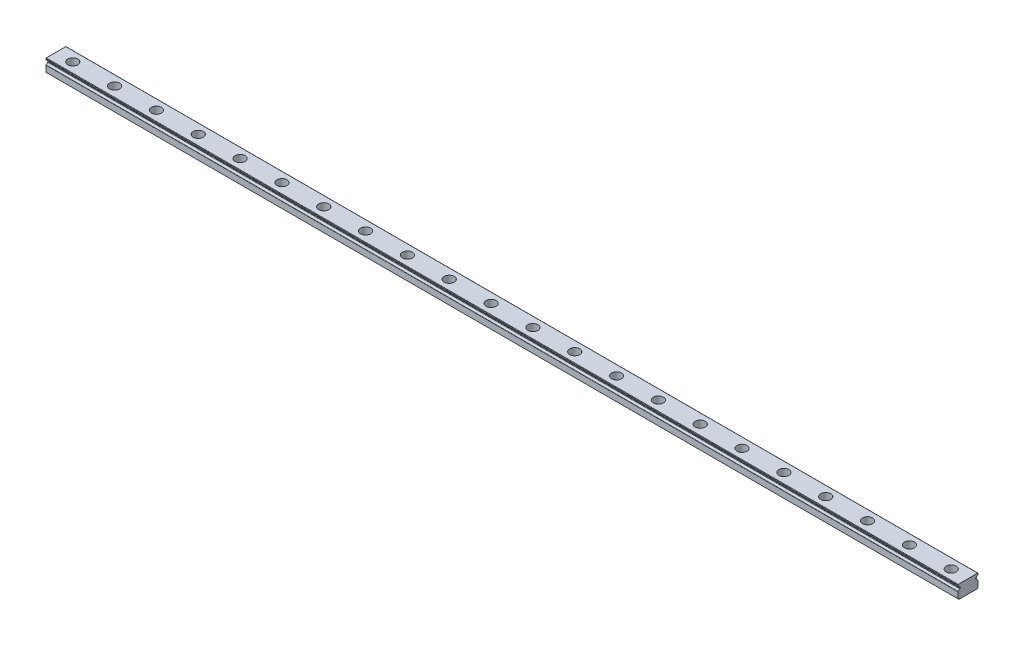
SolidWorks part; units mm, degrees
ref_plane "前视基准面" through (0, 0, 0) normal (0, 0, 1) x (1, 0, 0)
ref_plane "上视基准面" through (0, 0, 0) normal (0, 1, 0) x (1, 0, 0)
ref_plane "右视基准面" through (0, 0, 0) normal (1, 0, 0) x (0, 0, -1)
other "Configuration Table"
ref_plane "基准面1" through (0, 4, 0) normal (0, 1, 0) x (1, 0, 0)
sketch "草图1" plane through (0, 4, 0) normal (0, 1, 0) x (1, 0, 0)
  line L0 (272.5, -6) -> (272.5, 6)
  line L1 (272.5, 6) -> (-272.5, 6)
  line L2 (-272.5, 6) -> (-272.5, -6)
  line L3 (-272.5, -6) -> (272.5, -6)
extrude "凸台-拉伸1" add sketch "草图1" against normal blind 8
sketch "草图2" plane through (272.5, 0, 0) normal (1, 0, 0) x (0, 0, -1)
  line L0 (6, 1.51) -> (6, 2.01)
  line L1 (6, 2.01) -> (4.8, 2.01)
  line L2 (4.8, 1.51) -> (6, 1.51)
  arc A0 (4.8, 2.01) -> (4.8, 1.51) centre (4.8, 1.76) ccw
extrude "切除-拉伸1" cut sketch "草图2" against normal through all
sketch "草图3" plane through (272.5, 0, 0) normal (1, 0, 0) x (0, 0, -1)
  line L0 (6, 2.01) -> (6, 3.1111)
  line L1 (5.04, 2.01) -> (6, 2.01)
  arc A0 (6, 3.1111) -> (5.04, 2.01) centre (6.4382, 1.76) ccw
extrude "切除-拉伸2" cut sketch "草图3" against normal through all
sketch "草图4" plane through (272.5, 0, 0) normal (1, 0, 0) x (0, 0, -1)
  line L0 (6, 1.51) -> (5.04, 1.51)
  line L1 (6, 0.4089) -> (6, 1.51)
  arc A0 (5.04, 1.51) -> (6, 0.4089) centre (6.4382, 1.76) ccw
extrude "切除-拉伸3" cut sketch "草图4" against normal through all
sketch "草图5" plane through (272.5, 0, 0) normal (1, 0, 0) x (0, 0, -1)
  line L0 (-6, 2.01) -> (-6, 1.51)
  line L1 (-6, 1.51) -> (-4.8, 1.51)
  line L2 (-4.8, 2.01) -> (-6, 2.01)
  arc A0 (-4.8, 1.51) -> (-4.8, 2.01) centre (-4.8, 1.76) ccw
extrude "切除-拉伸4" cut sketch "草图5" against normal through all
sketch "草图6" plane through (272.5, 0, 0) normal (1, 0, 0) x (0, 0, -1)
  line L0 (-6, 1.51) -> (-6, 0.4089)
  line L1 (-5.04, 1.51) -> (-6, 1.51)
  arc A0 (-6, 0.4089) -> (-5.04, 1.51) centre (-6.4382, 1.76) ccw
extrude "切除-拉伸5" cut sketch "草图6" against normal through all
sketch "草图7" plane through (272.5, 0, 0) normal (1, 0, 0) x (0, 0, -1)
  line L0 (-6, 2.01) -> (-5.04, 2.01)
  line L1 (-6, 3.1111) -> (-6, 2.01)
  arc A0 (-5.04, 2.01) -> (-6, 3.1111) centre (-6.4382, 1.76) ccw
extrude "切除-拉伸6" cut sketch "草图7" against normal through all
hole_wizard "M3 六角头机械螺钉的柱形沉头孔1" positions "草图9" profile "草图8" counterbore size "M3" standard "ANSI Metric"
sketch "草图9" plane through (0, 4, 0) normal (0, 1, 0) x (1, 0, 0)
  point P0 (-262.5, 0)
  point P1 (-237.5, 0)
  point P2 (-212.5, 0)
  point P3 (-187.5, 0)
  point P4 (-162.5, 0)
  point P5 (-137.5, 0)
  point P6 (-112.5, 0)
  point P7 (-87.5, 0)
  point P8 (-62.5, 0)
  point P9 (-37.5, 0)
  point P10 (-12.5, 0)
  point P11 (12.5, 0)
  point P12 (37.5, 0)
  point P13 (62.5, 0)
  point P14 (87.5, 0)
  point P15 (112.5, 0)
  point P16 (137.5, 0)
  point P17 (162.5, 0)
  point P18 (187.5, 0)
  point P19 (212.5, 0)
  point P20 (237.5, 0)
  point P21 (262.5, 0)
sketch "草图8" plane through (-262.5, 4, 0) normal (1, 0, 0) x (0, 0, 1)
  line L0 (0, 0) -> (0, 8)
  line L1 (0, 8) -> (1.75, 8)
  line L3 (1.75, 8) -> (1.75, 4.5)
  line L4 (1.75, 4.5) -> (2.9999, 4.5)
  line L5 (2.9999, 4.5) -> (2.9999, 0)
  line L7 (2.9999, 0) -> (0, 0)
  line L11 (0, -6.35) -> (0, 107.95) construction
  dimension "通孔孔直径" = 3.5
  dimension "通孔孔深度" = 8
  dimension "柱形沉头孔直径" = 5.9999
  dimension "柱形沉头孔深度" = 4.5
chamfer "倒角1" distance 0.6 angle 45 2 edges at (0, -4, -6) (0, -4, 6)
fillet "圆角1" radius 0.2 10 edges at (0, 3.1111, -6) (0, 1.51, -5.04) (0, 4, -6) (0, 1.51, 5.04) (0, 2.01, -5.04) (0, 2.01, 5.04) (0, 4, 6) (0, 3.1111, 6) (0, 0.4089, -6) (0, 0.4089, 6)
